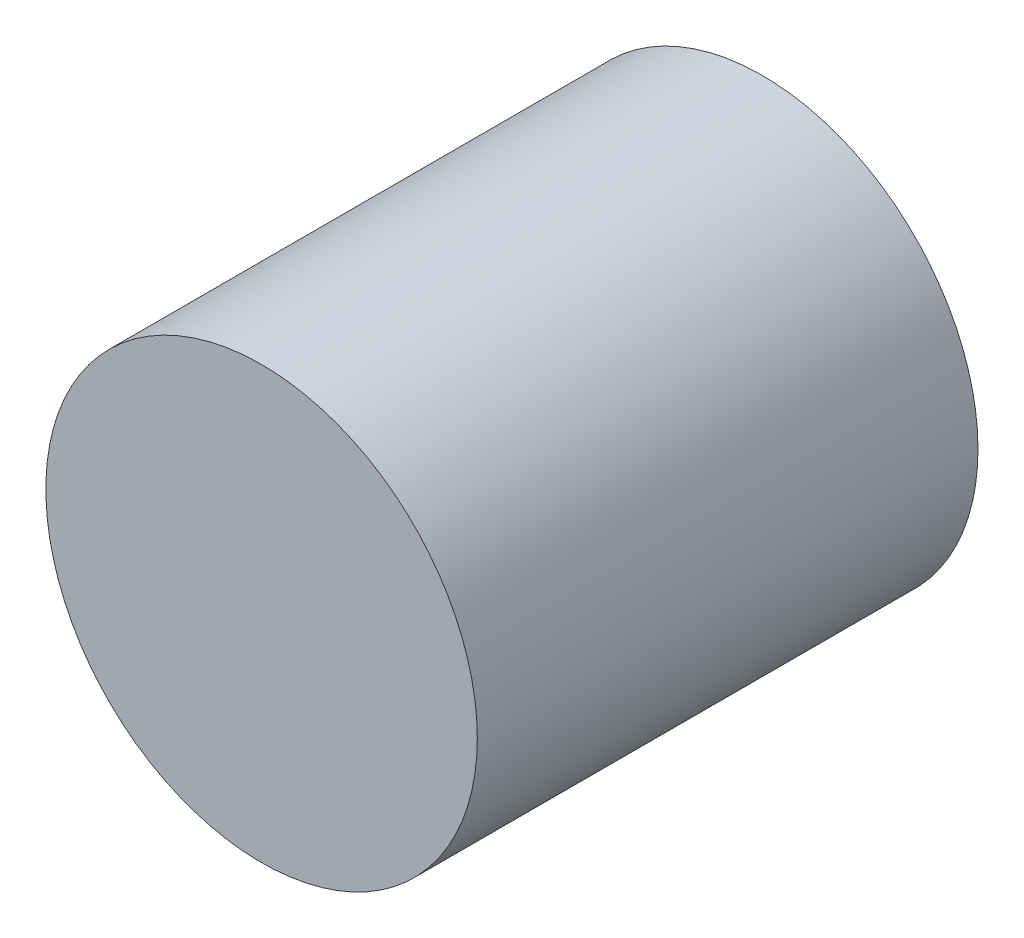
SolidWorks part; units mm, degrees
ref_plane "Plan de face" through (0, 0, 0) normal (0, 0, 1) x (1, 0, 0)
ref_plane "Plan de dessus" through (0, 0, 0) normal (0, 1, 0) x (1, 0, 0)
ref_plane "Plan de droite" through (0, 0, 0) normal (1, 0, 0) x (0, 0, -1)
sketch "Esquisse1" plane through (0, 0, 0) normal (0, 0, 1) x (1, 0, 0)
  circle A0 centre (0, 0) radius 30.1604
extrude "Boss.-Extru.1" add sketch "Esquisse1" along normal blind 70
hole_wizard "Trou taraudé 1 Rc1" positions "Esquisse3D4" profile "Esquisse10" size "1" standard "ISO"
sketch3d "Esquisse3D4"
  point P0 (0.0415, 0.4983, 0)
  point P2 (41.4843, -12.7069, 0)
sketch "Esquisse10" plane through (0.0415, 0.4983, 0) normal (1, 0, 0) x (0, 1, 0)
  line L0 (0, 0) -> (0, 18.5154)
  line L1 (17.5005, 8) -> (0, 18.5154)
  line L2 (-17.5005, 8) -> (0, 18.5154) construction
  line L3 (17.5005, 8) -> (17.5005, 0.1)
  line L4 (17.5005, 0.1) -> (16.0283, 0.1)
  line L5 (16.0283, 0.1) -> (16.0314, 0)
  line L6 (-16.0283, 0.1) -> (-16.0314, 0) construction
  line L7 (16.0314, 0) -> (0, 0)
  line L8 (0, -6.35) -> (0, 107.95) construction
  line L11 (-17.5005, 0.1) -> (-16.0283, 0.1) construction
  dimension "Diamètre du trou pour taraudage" = 35.001
  dimension "Profondeur du trou pour taraudage" = 8
  dimension "Diamètre du filetage" = 32.0628
  dimension "Angle de filetage" = 3.576
  dimension "Profondeur du filetage" = 0.1
  dimension "Angle de pointe" = 118
